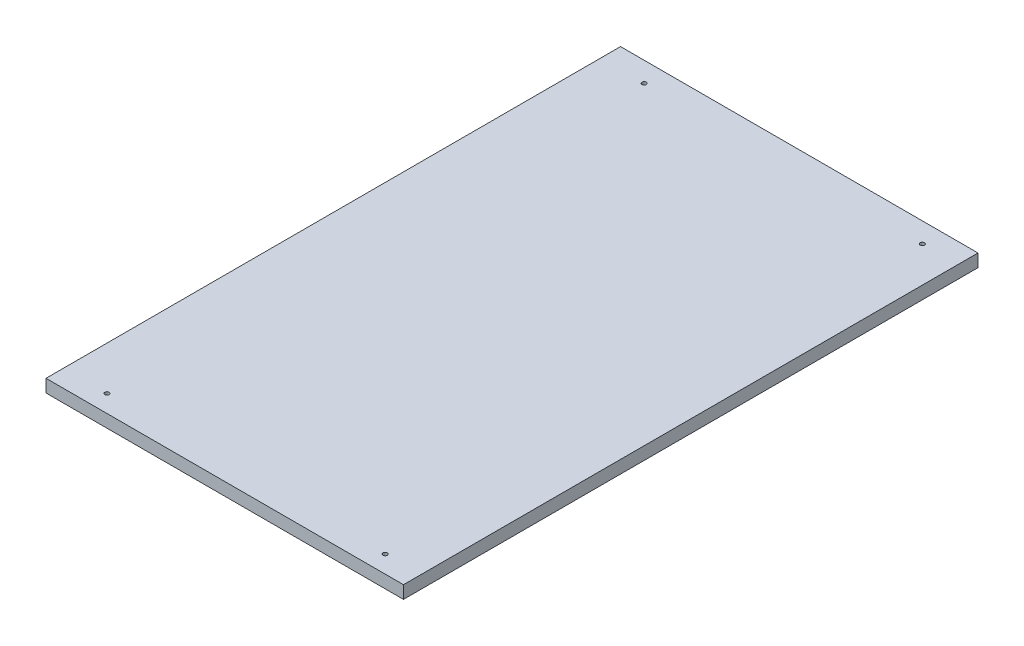
SolidWorks part; units mm, degrees
material "Homopolímero PP"
ref_plane "Plano frontal" through (0, 0, 0) normal (0, 0, 1) x (1, 0, 0)
ref_plane "Plano superior" through (0, 0, 0) normal (0, 1, 0) x (1, 0, 0)
ref_plane "Plano direito" through (0, 0, 0) normal (1, 0, 0) x (0, 0, -1)
sketch "Esboço1" plane through (0, 0, 0) normal (0, 1, 0) x (1, 0, 0)
  line L0 (-830.4514, 0) -> (40692.1163, 0) construction
  line L1 (0, -830.4514) -> (0, 40692.1163) construction
  line L2 (-42, 67.5) -> (42, 67.5)
  line L3 (42, 67.5) -> (42, -67.5)
  line L4 (42, -67.5) -> (-42, -67.5)
  line L5 (830.4514, 0) -> (-40692.1163, 0) construction
  line L6 (-42, 67.5) -> (-42, -67.5)
  point P4 (0, -67.5)
  point P13 (0, 67.5)
  dimension "D1" = 42
  dimension "D2" = 135
extrude "Ressalto-extrusão1" add sketch "Esboço1" along normal blind 3
hole_wizard "Furos-guia com Ø1.0mm4" positions "Esboço17" profile "Esboço18" hole size "Ø1.0" standard "Ansi Metric"
sketch "Esboço17" plane through (0, 3, 0) normal (0, 1, 0) x (1, 0, 0)
  point P0 (-31.7496, 62.8017)
  point P2 (33.6216, 62.8017)
  point P4 (-31.7496, -63.4293)
  point P6 (33.6216, -63.4293)
sketch "Esboço18" plane through (-31.7496, 3, -62.8017) normal (1, 0, 0) x (0, 0, 1)
  line L0 (0, 0) -> (0, 3.3004)
  line L1 (0, 3.3004) -> (0.5, 3)
  line L2 (0.5, 3) -> (0.5, 0)
  line L5 (0.5, 0) -> (0, 0)
  line L10 (0, 3.3004) -> (-0.5, 3) construction
  line L11 (0, -6.35) -> (0, 107.95) construction
  dimension "Hole Dia." = 1
  dimension "Hole Depth" = 3
  dimension "Drill Angle" = 118
